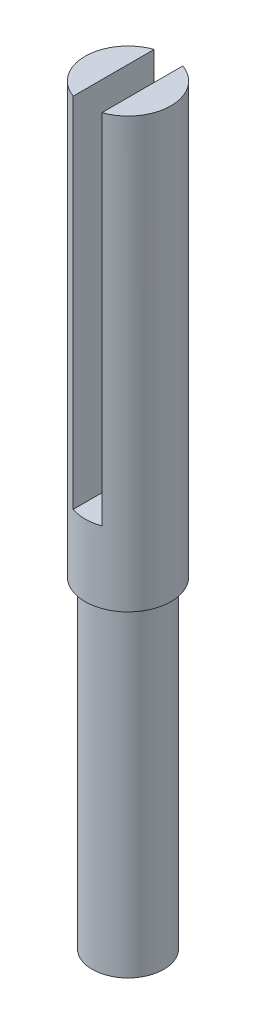
SolidWorks part; units mm, degrees
material "Galvanized Steel"
ref_plane "Front Plane" through (0, 0, 0) normal (0, 0, 1) x (1, 0, 0)
ref_plane "Top Plane" through (0, 0, 0) normal (0, 1, 0) x (1, 0, 0)
ref_plane "Right Plane" through (0, 0, 0) normal (1, 0, 0) x (0, 0, -1)
sketch "Sketch1" plane through (0, 0, 0) normal (0, 1, 0) x (1, 0, 0)
  circle A0 centre (0, 0) radius 6
  dimension "D1" = 12
extrude "Boss-Extrude1" add sketch "Sketch1" along normal blind 5
sketch "Sketch2" plane through (0, 0, 0) normal (0, -1, 0) x (1, 0, 0)
  circle A0 centre (0, 0) radius 6
  dimension "D1" = 12
extrude "Boss-Extrude2" add sketch "Sketch2" along normal blind 100
sketch "Sketch3" plane through (0, 0, 0) normal (0, 0, 1) x (1, 0, 0)
  line L1 (-2, 5) -> (2, 5)
  line L2 (-2, 5) -> (-2, -45)
  line L3 (-2, -45) -> (2, -45)
  line L4 (2, 5) -> (2, -45)
  line L5 (6, 5) -> (-6, 5) construction
  point P8 (0, 5)
  dimension "D2" = 2
  dimension "D3" = 50
extrude "Cut-Extrude1" cut sketch "Sketch3" against normal through all both and the other way through all
sketch "Sketch4" plane through (0, -100, 0) normal (0, -1, 0) x (1, 0, 0)
  circle A0 centre (0, 0) radius 5
  circle A1 centre (0, 0) radius 6
  dimension "D1" = 10
extrude "Cut-Extrude2" cut sketch "Sketch4" against normal blind 45
